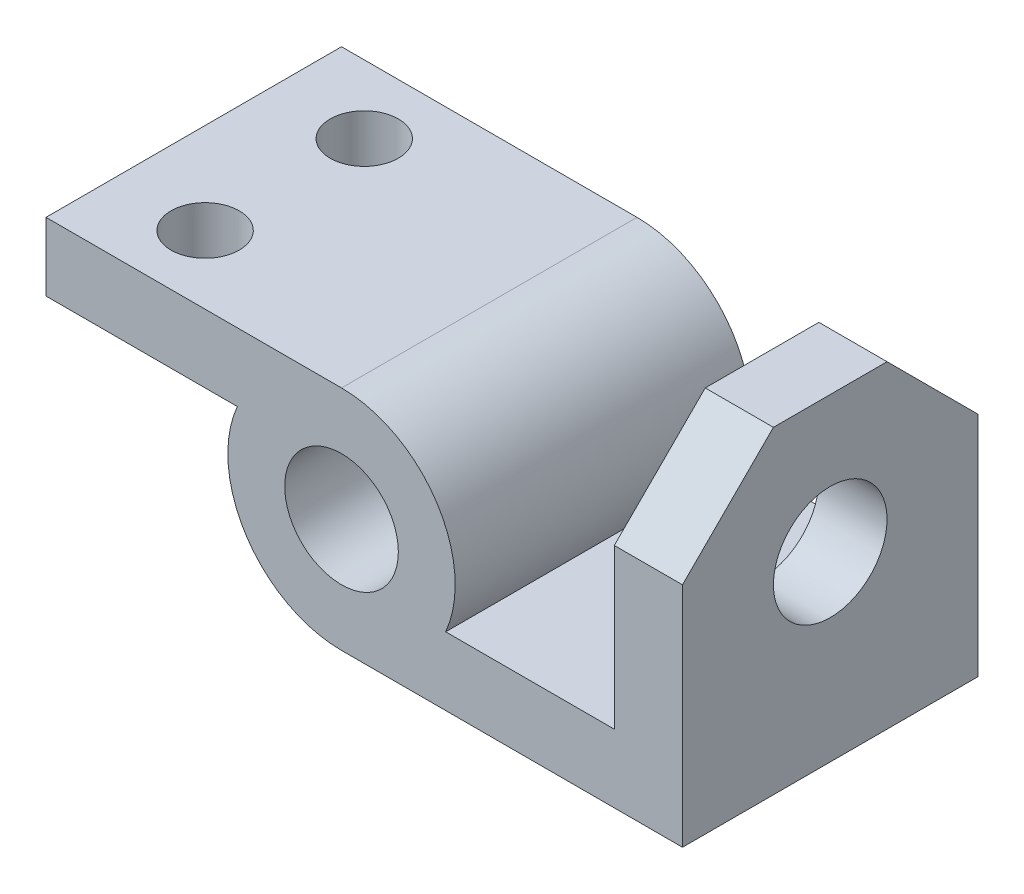
SolidWorks part; units mm, degrees
ref_plane "Front Plane" through (0, 0, 0) normal (0, 0, 1) x (1, 0, 0)
ref_plane "Top Plane" through (0, 0, 0) normal (0, 1, 0) x (1, 0, 0)
ref_plane "Right Plane" through (0, 0, 0) normal (1, 0, 0) x (0, 0, -1)
sketch "Sketch1" plane through (0, 0, 0) normal (0, 0, 1) x (1, 0, 0)
  line L0 (0, 31.75) -> (-82.55, 31.75)
  line L1 (-82.55, 31.75) -> (-82.55, 12.7)
  line L2 (-82.55, 12.7) -> (-29.0994, 12.7)
  line L3 (0, -31.75) -> (95.25, -31.75)
  line L5 (76.2, -12.7) -> (29.0994, -12.7)
  line L6 (76.2, -12.7) -> (76.2, 57.15)
  line L7 (76.2, 57.15) -> (95.25, 57.15)
  line L8 (95.25, 57.15) -> (95.25, -31.75)
  arc A0 (-29.0994, 12.7) -> (0, -31.75) centre (0, 0) ccw
  arc A1 (29.0994, -12.7) -> (0, 31.75) centre (0, 0) ccw
  point P13 (95.25, 78.6608)
  point P14 (95.25, -30.3488)
  dimension "D1" = 63.5
  dimension "D2" = 82.55
  dimension "D3" = 19.05
  dimension "D4" = 95.25
  dimension "D5" = 88.9
  dimension "D6" = 47.1006
  dimension "D7" = 19.05
extrude "Boss-Extrude1" add sketch "Sketch1" along normal mid plane 82.55
sketch "Sketch2" plane through (0, 31.75, 0) normal (0, 1, 0) x (1, 0, 0)
  line L0 (0, 41.275) -> (-82.55, 41.275) construction
  line L1 (-82.55, -41.275) -> (-82.55, 41.275) construction
  line L2 (-113.1306, 0) -> (108.5855, 0) construction
  circle A0 centre (-57.15, 22.225) radius 9.525
  circle A1 centre (-57.15, -22.225) radius 9.525
  dimension "D3" = 19.05
  dimension "D1" = 19.05
  dimension "D2" = 25.4
extrude "Cut-Extrude1" cut sketch "Sketch2" against normal through all
sketch "Sketch3" plane through (95.25, 0, 0) normal (1, 0, 0) x (0, 0, -1)
  line L0 (-41.275, -31.75) -> (41.275, -31.75) construction
  line L2 (0, 73.872) -> (0, -52.7217) construction
  circle A0 centre (0, 19.05) radius 15.875
  dimension "D1" = 31.75
  dimension "D2" = 50.8
extrude "Cut-Extrude2" cut sketch "Sketch3" against normal up to next
chamfer "Chamfer1" distance 25.4 distance2 25.4 2 edges at (85.725, 57.15, -41.275) (85.725, 57.15, 41.275)
sketch "Sketch4" plane through (0, 0, 41.275) normal (0, 0, 1) x (1, 0, 0)
  circle A0 centre (0, 0) radius 15.875
  dimension "D1" = 31.75
extrude "Cut-Extrude3" cut sketch "Sketch4" against normal blind 82.55
